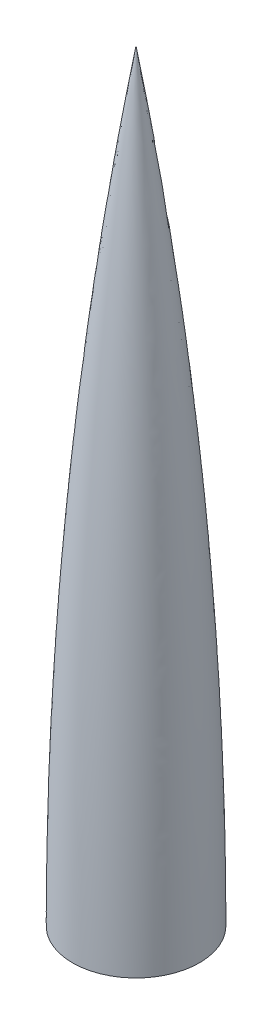
SolidWorks part; units mm, degrees
material "A-Glass Fiber"
ref_plane "Front Plane" through (0, 0, 0) normal (0, 0, 1) x (1, 0, 0)
ref_plane "Top Plane" through (0, 0, 0) normal (0, 1, 0) x (1, 0, 0)
ref_plane "Right Plane" through (0, 0, 0) normal (1, 0, 0) x (0, 0, -1)
sketch "Sketch1" plane through (0, 0, 0) normal (0, 0, 1) x (1, 0, 0)
  line L0 (0, 0) -> (-49.53, 0) construction
  line L1 (-49.53, 0) -> (-50.8, 0)
  line L2 (-50.8, -33.7223) -> (-50.8, 0) construction
  line L3 (0, 609.6) -> (0, 0) construction
  line L6 (-10.6863, 533.4) -> (-11.9698, 533.4)
  line L7 (-10.6863, 533.4) -> (0, 533.4) construction
  arc A0 (-50.8, 0) -> (0, 609.6) centre (3632.2, 0) cw construction
  arc A1 (-49.53, 0) -> (0, 601.8795) centre (3632.2, 0) cw construction
  arc A6 (-11.9698, 533.4) -> (-50.8, 0) centre (3632.2, 0) ccw
  arc A7 (-10.6863, 533.4) -> (-49.53, 0) centre (3632.2, 0) ccw
  dimension "D1" = 50.8
  dimension "D2" = 49.53
  dimension "D3" = 609.6
  dimension "D4" = 76.2
revolve "Revolve3" add sketch "Sketch1" angle 360 about L3
sketch "Sketch3" plane through (0, 0, 0) normal (0, 0, 1) x (1, 0, 0)
  line L0 (0, 0) -> (-49.53, 0) construction
  line L1 (-49.53, 0) -> (-50.8, 0)
  line L2 (-50.8, -33.7223) -> (-50.8, 0) construction
  line L3 (0, 609.6) -> (0, 0) construction
  line L7 (-11.9698, 533.4) -> (0, 533.4)
  line L8 (10.6863, 533.4) -> (-10.6863, 533.4) construction
  line L9 (0, 533.4) -> (0, 609.6)
  arc A0 (-50.8, 0) -> (0, 609.6) centre (3632.2, 0) cw construction
  arc A8 (-11.9698, 533.4) -> (0, 609.6) centre (3632.2, 0) cw
  point P4 (-12.1194, 533.4)
  point P6 (0, 0)
  point P8 (-11.9698, 533.4)
  point P15 (-0.218, 610.9595)
  point P16 (0, 593.6258)
  point P17 (0, 570.5547)
  dimension "D1" = 50.8
  dimension "D2" = 49.53
  dimension "D3" = 609.6
revolve "Revolve4" add sketch "Sketch3" angle 360 about L9
